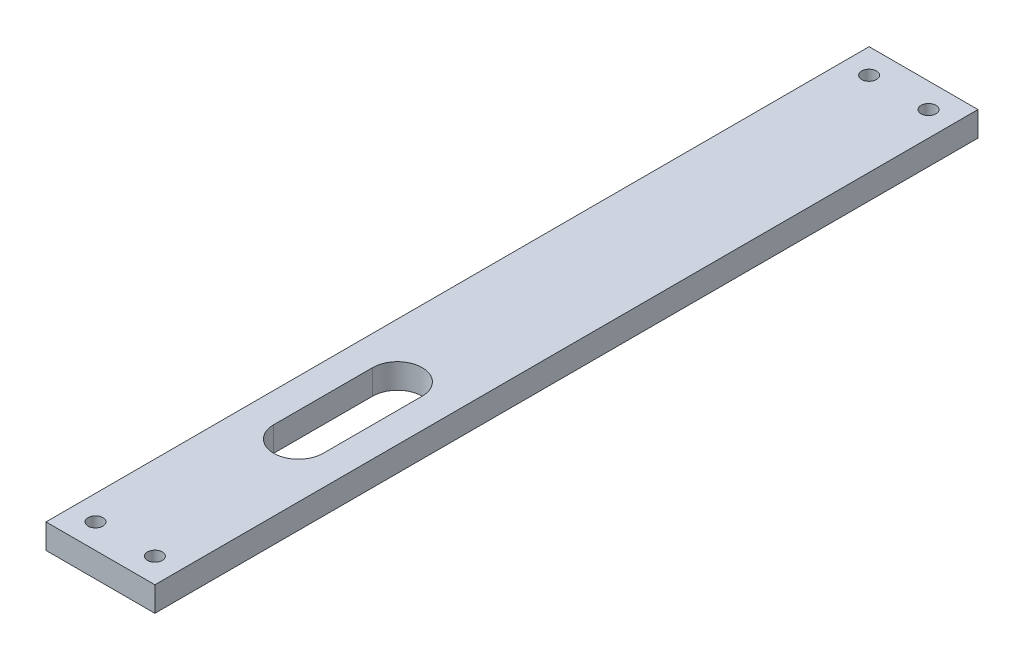
SolidWorks part; units mm, degrees
ref_plane "Front" through (0, 0, 0) normal (0, 0, 1) x (1, 0, 0)
ref_plane "Top" through (0, 0, 0) normal (0, 1, 0) x (1, 0, 0)
ref_plane "Right" through (0, 0, 0) normal (1, 0, 0) x (0, 0, -1)
sketch "Sketch1" plane through (0, 0, 0) normal (0, 1, 0) x (1, 0, 0)
  line L0 (11, 166.3) -> (11, 161.3)
  line L1 (0, 0) -> (22, 0)
  line L2 (0, 0) -> (0, 166.3)
  line L3 (0, 166.3) -> (22, 166.3)
  line L4 (22, 0) -> (22, 166.3)
  line L5 (5, 161.3) -> (17, 161.3)
  line L6 (0, 83.15) -> (22, 83.15)
  circle A0 centre (5, 161.3) radius 1.5
  circle A1 centre (17, 161.3) radius 1.5
  circle A2 centre (17, 5) radius 1.5
  circle A3 centre (5, 5) radius 1.5
  point P10 (11, 161.3)
  dimension "D1" = 166.3
  dimension "D2" = 22
  dimension "D3" = 12
extrude "Boss-Extrude1" add sketch "Sketch1" along normal blind 5
sketch "Sketch2" plane through (0, 0, 0) normal (0, -1, 0) x (-1, 0, 0)
  line L0 (-11, 0) -> (-11, 40)
  line L1 (0, 0) -> (-22, 0) construction
  line L2 (-11, 40) -> (-11, 60)
  line L3 (-11, 40) -> (-11, 60) construction
  line L4 (-16, 40) -> (-16, 60)
  line L5 (-6, 40) -> (-6, 60)
  arc A0 (-16, 40) -> (-6, 40) centre (-11, 40) ccw
  arc A1 (-6, 60) -> (-16, 60) centre (-11, 60) ccw
  point P5 (-11, 50)
  dimension "D3" = 5
  dimension "D1" = 40
  dimension "D2" = 20
extrude "Cut-Extrude1" cut sketch "Sketch2" against normal blind 5
